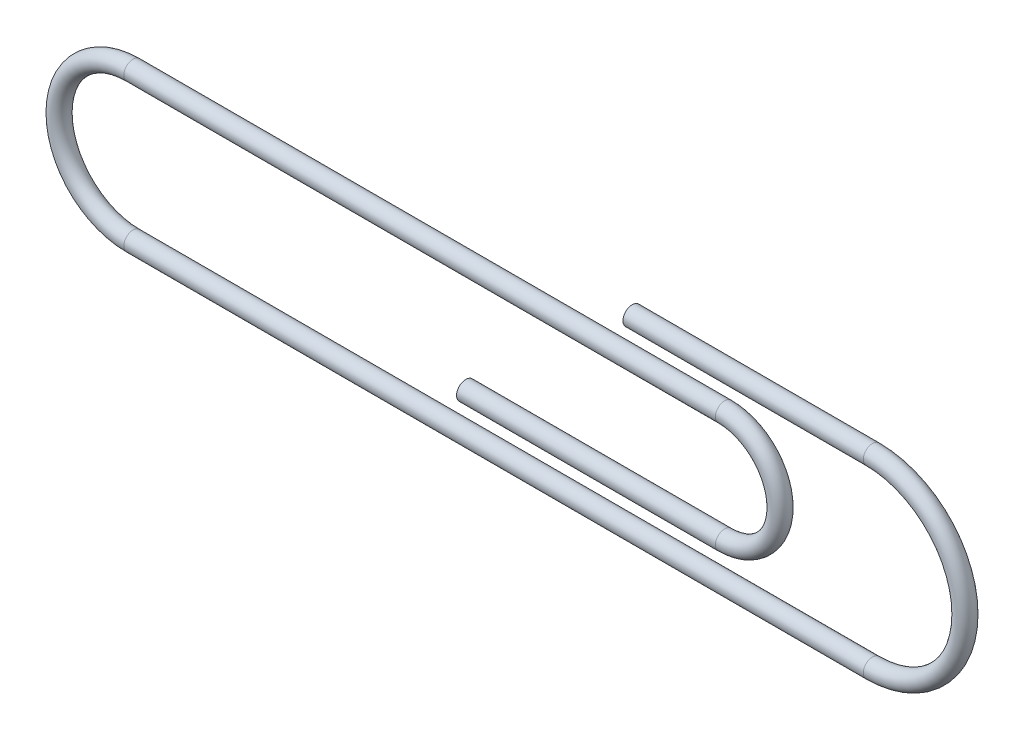
SolidWorks part; units mm, degrees
ref_plane "Front Plane" through (0, 0, 0) normal (0, 0, 1) x (1, 0, 0)
ref_plane "Top Plane" through (0, 0, 0) normal (0, 1, 0) x (1, 0, 0)
ref_plane "Right Plane" through (0, 0, 0) normal (1, 0, 0) x (0, 0, -1)
sketch "Sketch1" plane through (0, 0, 0) normal (0, 0, 1) x (1, 0, 0)
  line L0 (0, 0) -> (70, 0)
  line L2 (70, 30) -> (-90, 30)
  line L4 (-90, -10) -> (110, -10)
  line L6 (110, 40) -> (45, 40)
  arc A1 (70, 0) -> (70, 30) centre (70, 15) ccw
  arc A2 (110, -10) -> (110, 40) centre (110, 15) ccw
  arc A3 (-90, 30) -> (-90, -10) centre (-90, 10) ccw
  dimension "D1" = 70
  dimension "D2" = 30
  dimension "D3" = 160
  dimension "D4" = 40
  dimension "D5" = 200
  dimension "D6" = 50
  dimension "D7" = 65
sketch "Sketch2" plane through (0, 0, 0) normal (1, 0, 0) x (0, 0, -1)
  circle A0 centre (0, 0) radius 2.5
  dimension "D1" = 5
sweep "Sweep1" add profiles "Sketch2" path "Sketch1"
